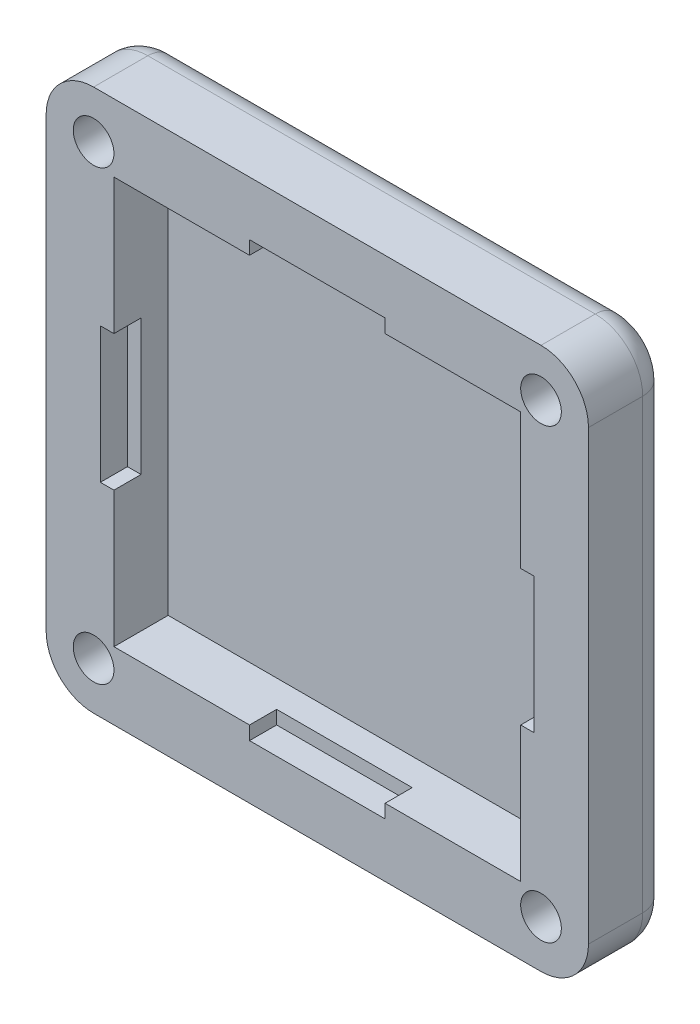
SolidWorks part; units mm, degrees
ref_plane "Front Plane" through (0, 0, 0) normal (0, 0, 1) x (1, 0, 0)
ref_plane "Top Plane" through (0, 0, 0) normal (0, 1, 0) x (1, 0, 0)
ref_plane "Right Plane" through (0, 0, 0) normal (1, 0, 0) x (0, 0, -1)
sketch "Sketch1" plane through (0, 0, 0) normal (0, 0, 1) x (1, 0, 0)
  line L1 (0, 0) -> (40, 0)
  line L2 (0, 0) -> (0, 40)
  line L3 (0, 40) -> (40, 40)
  line L4 (40, 0) -> (40, 40)
  dimension "D1" = 40
  dimension "D2" = 40
extrude "Boss-Extrude1" add sketch "Sketch1" along normal blind 2
sketch "Sketch2" plane through (0, 0, 2) normal (0, 0, 1) x (1, 0, 0)
  line L0 (40, 0) -> (40, 40) construction
  line L1 (0, 40) -> (40, 40)
  line L2 (0, 40) -> (0, 0)
  line L3 (0, 0) -> (40, 0)
  line L4 (40, 40) -> (40, 0)
  line L6 (5, 35) -> (35, 35)
  line L7 (5, 35) -> (5, 5)
  line L8 (5, 5) -> (35, 5)
  line L9 (35, 35) -> (35, 5)
  dimension "D1" = 30
  dimension "D2" = 30
  dimension "D3" = 5
  dimension "D4" = 5
extrude "Boss-Extrude2" add sketch "Sketch2" along normal blind 2
sketch "Sketch3" plane through (0, 0, 4) normal (0, 0, 1) x (1, 0, 0)
  line L1 (0, 40) -> (40, 40)
  line L2 (0, 40) -> (0, 0)
  line L3 (0, 0) -> (40, 0)
  line L4 (40, 40) -> (40, 0)
  line L5 (4, 36) -> (36, 36)
  line L6 (4, 36) -> (4, 4)
  line L7 (4, 4) -> (36, 4)
  line L8 (36, 36) -> (36, 4)
  line L9 (5, 35) -> (35, 35)
  line L10 (5, 35) -> (5, 5)
  line L11 (5, 5) -> (35, 5)
  line L12 (35, 35) -> (35, 5)
  line L13 (15, 36) -> (25, 36)
  line L14 (15, 36) -> (15, 35)
  line L15 (15, 35) -> (25, 35)
  line L16 (25, 36) -> (25, 35)
  line L17 (4, 25) -> (5, 25)
  line L18 (4, 25) -> (4, 15)
  line L19 (4, 15) -> (5, 15)
  line L20 (5, 25) -> (5, 15)
  line L21 (35, 25) -> (36, 25)
  line L22 (35, 25) -> (35, 15)
  line L23 (35, 15) -> (36, 15)
  line L24 (36, 25) -> (36, 15)
  line L25 (15, 5) -> (25, 5)
  line L26 (15, 5) -> (15, 4)
  line L27 (15, 4) -> (25, 4)
  line L28 (25, 5) -> (25, 4)
  point P32 (4.5, 15)
  point P33 (25, 35.5)
  line M7 (0, 40) -> (0, 0)
  line M8 (0, 0) -> (40, 0)
  line M9 (40, 0) -> (40, 40)
  line M10 (40, 40) -> (0, 40)
  line M11 (35, 5) -> (5, 5)
  line M12 (5, 5) -> (5, 35)
  line M13 (5, 35) -> (35, 35)
  line M14 (35, 35) -> (35, 5)
  dimension "D1" = 32
  dimension "D2" = 4
  dimension "D3" = 32
  dimension "D4" = 4
  dimension "D5" = 11
  dimension "D6" = 10
  dimension "D7" = 11
  dimension "D8" = 10
  dimension "D9" = 11
  dimension "D10" = 10
  dimension "D11" = 11
  dimension "D12" = 10
extrude "Boss-Extrude3" add sketch "Sketch3" along normal blind 2 contours L5 L8 L7 L6 M10 M7 M8 M9 | L6 L17 L10 L14 L5 M13 | L21 L8 L5 L16 M14 M13 | L28 L7 L8 L23 M11 M14 | L26 L19 L6 L7 M11 M12
sketch "Sketch4" plane through (0, 0, 6) normal (0, 0, 1) x (1, 0, 0)
  line L0 (0, 40) -> (0, 0) construction
  line L1 (40, 40) -> (0, 40) construction
  line L3 (40, 0) -> (40, 40) construction
  line L4 (0, 0) -> (40, 0) construction
  circle A0 centre (3.5, 36.5) radius 1.5
  circle A1 centre (36.5, 36.5) radius 1.5
  circle A2 centre (36.5, 3.5) radius 1.5
  circle A3 centre (3.5, 3.5) radius 1.5
  dimension "D1" = 3
  dimension "D2" = 3
  dimension "D3" = 3
  dimension "D4" = 3
  dimension "D12" = 3.5
  dimension "D5" = 3.5
  dimension "D6" = 3.5
  dimension "D7" = 3.5
  dimension "D8" = 3.5
  dimension "D9" = 3.5
  dimension "D10" = 3.5
  dimension "D11" = 3.5
extrude "Cut-Extrude1" cut sketch "Sketch4" against normal blind 4
fillet "Fillet1" radius 3.5 4 edges at (0, 0, 3) (40, 0, 3) (40, 40, 3) (0, 40, 3)
fillet "Fillet2" radius 2 8 edges at (38.9749, 38.9749, 0) (40, 20, 0) (38.9749, 1.0251, 0) (20, 0, 0) (1.0251, 1.0251, 0) (0, 20, 0) (1.0251, 38.9749, 0) (20, 40, 0)
